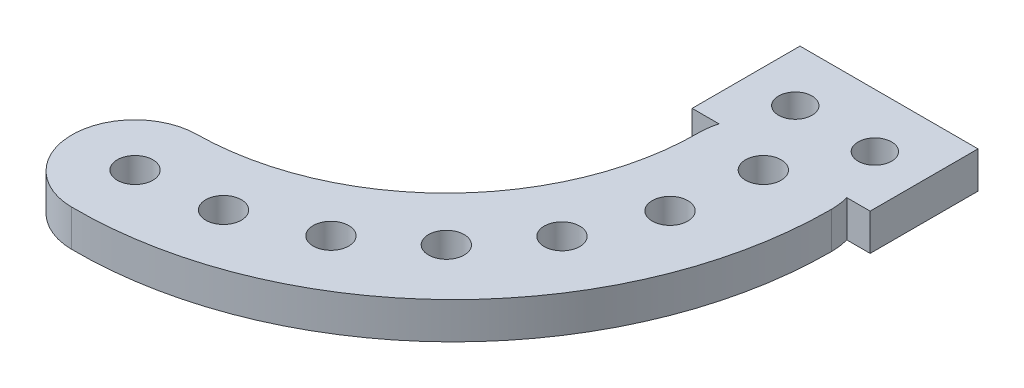
SolidWorks part; units mm, degrees
ref_plane "Plano frontal" through (0, 0, 0) normal (0, 0, 1) x (1, 0, 0)
ref_plane "Plano superior" through (0, 0, 0) normal (0, 1, 0) x (1, 0, 0)
ref_plane "Plano direito" through (0, 0, 0) normal (1, 0, 0) x (0, 0, -1)
sketch "Esboço1" plane through (0, 0, 0) normal (0, 1, 0) x (1, 0, 0)
  line L1 (-25, 5.5) -> (25, 5.5)
  line L2 (-25, 5.5) -> (-25, -5.5)
  line L3 (-25, -5.5) -> (25, -5.5)
  line L4 (25, 5.5) -> (25, -5.5)
  line L5 (-25, 5.5) -> (25, -5.5) construction
  line L6 (-25, -5.5) -> (25, 5.5) construction
  point P0 (0, 0)
  dimension "D1" = 50
  dimension "D2" = 11
extrude "Ressalto-extrusão1" add sketch "Esboço1" along normal blind 22.5
sketch "Esboço2" plane through (0, 22.5, 0) normal (0, 1, 0) x (1, 0, 0)
  line L1 (-23, 3.5) -> (23, 3.5)
  line L2 (-23, 3.5) -> (-23, -3.5)
  line L3 (-23, -3.5) -> (23, -3.5)
  line L4 (23, 3.5) -> (23, -3.5)
  line L5 (-23, 3.5) -> (23, -3.5) construction
  line L6 (-23, -3.5) -> (23, 3.5) construction
  point P0 (0, 0)
extrude "Corte-extrusão1" cut sketch "Esboço2" against normal blind 20.5
sketch "Esboço3" plane through (0, 22.5, 0) normal (0, 1, 0) x (1, 0, 0)
  line L3 (23, 3.5) -> (-23, 3.5) construction
  line L4 (-5.4896, 5.5) -> (5.4896, 5.5)
  line L5 (-5.4896, 5.5) -> (-5.4896, 3.5)
  line L6 (-5.4896, 3.5) -> (5.4896, 3.5)
  line L7 (5.4896, 5.5) -> (5.4896, 3.5)
  line L8 (-5.4896, 5.5) -> (5.4896, 3.5) construction
  line L9 (-5.4896, 3.5) -> (5.4896, 5.5) construction
  point P6 (0, 4.5)
extrude "Corte-extrusão2" cut sketch "Esboço3" against normal blind 4
sketch "Esboço5" plane through (0, 0, 5.5) normal (0, 0, 1) x (1, 0, 0)
  line L0 (-25, 22.5) -> (25, 22.5) construction
  line L1 (-21, 22.5) -> (-4.5, 22.5)
  line L2 (-21, 22.5) -> (-21, 11.75)
  line L4 (-4.5, 22.5) -> (-4.5, 11.75)
  line L5 (-25, 22.5) -> (-25, 0) construction
  line L7 (4.5, 22.5) -> (21, 22.5)
  line L8 (4.5, 22.5) -> (4.5, 11.75)
  line L10 (21, 22.5) -> (21, 11.75)
  line L11 (25, 22.5) -> (25, 0) construction
  arc A0 (-21, 11.75) -> (-4.5, 11.75) centre (-12.75, 11.75) ccw
  arc A1 (4.5, 11.75) -> (21, 11.75) centre (12.75, 11.75) ccw
  dimension "D1" = 16.5
  dimension "D2" = 4
  dimension "D3" = 16.5
  dimension "D4" = 4
  dimension "D6" = 0
extrude "Corte-extrusão3" cut sketch "Esboço5" against normal blind 4
sketch "Esboço9" plane through (0, 0, -5.5) normal (0, 0, -1) x (-1, 0, 0)
  line L0 (25, 22.5) -> (25, 0) construction
  line L1 (-25, 0) -> (25, 0)
  line L2 (-25, 0) -> (-25, 4)
  line L3 (-25, 4) -> (25, 4)
  line L4 (25, 0) -> (25, 4)
  dimension "D1" = 4
extrude "Ressalto-extrusão4" add sketch "Esboço9" along normal blind 7
sketch "Esboço13" plane through (0, 4, 0) normal (0, 1, 0) x (1, 0, 0)
  line L0 (25, 12.5) -> (25, 5.5) construction
  circle A0 centre (10, 9) radius 1.5
  circle A1 centre (5, 9) radius 1.5
  circle A2 centre (20, 9) radius 1.5
  circle A3 centre (15, 9) radius 1.5
  circle A4 centre (0, 9) radius 1.5
  circle A5 centre (-5, 9) radius 1.5
  circle A6 centre (-10, 9) radius 1.5
  circle A7 centre (-15, 9) radius 1.5
  circle A8 centre (-20, 9) radius 1.5
extrude "Corte-extrusão4" cut sketch "Esboço13" against normal blind 7
sketch "Esboço19" plane through (0, 22.5, 0) normal (0, 1, 0) x (1, 0, 0)
  line L0 (4.5, -3.5) -> (4.5, -5.5) construction
  line L1 (-4.5, -3.5) -> (4.5, -3.5)
  line L2 (-4.5, -3.5) -> (-4.5, -7.5)
  line L3 (-4.5, -7.5) -> (4.5, -7.5)
  line L4 (4.5, -3.5) -> (4.5, -7.5)
  point P4 (4.5, -4.5)
  dimension "D1" = 4
  dimension "D2" = 0
extrude "Ressalto-extrusão5" add sketch "Esboço19" against normal blind 22.5
ref_plane "Plano1" through (0, 32.5, 0) normal (0, 1, 0) x (1, 0, 0)
sketch "Esboço20" plane through (0, 32.5, 0) normal (0, 1, 0) x (1, 0, 0)
  line L0 (-15, -21) -> (-15, -15.1047) construction
  line L1 (25.584, -30.2923) -> (-27.4052, -30.2923)
  line L2 (25.584, -30.2923) -> (25.584, 21.1444)
  line L3 (25.584, 21.1444) -> (-27.4052, 21.1444)
  line L4 (-27.4052, -30.2923) -> (-27.4052, 21.1444)
  line L5 (-15, -21) -> (-21, -21) construction
  line L6 (-15, -21) -> (-15, -27.0897) construction
  line L7 (15, 9) -> (21.5, 9) construction
  line L8 (15, 9) -> (15, 15) construction
  line L9 (15, 9) -> (8.8338, 9) construction
  circle A1 centre (15, 9) radius 1.7
  circle A2 centre (-15, 9) radius 1.5 construction
  circle A3 centre (-15, 9) radius 1.5
  arc A4 (15, 9) -> (-15, -21) centre (-15, 9) cw
  circle A6 centre (20, 9) radius 1.5 construction
  arc A7 (8.8338, 9) -> (21.5, 9) centre (15.1669, 9.0036) cw
  arc A8 (-15, -15.1047) -> (-15, -27.0897) centre (-14.9357, -21.0972) ccw
  arc A9 (8.8338, 9) -> (-15, -15.1047) centre (-15.2587, 8.9864) cw
  arc A10 (21.5, 9) -> (-15, -27.0897) centre (-14.6122, 9.0204) cw
  circle A11 centre (-15, -21) radius 1.7
extrude "Ressalto-extrusão7" add sketch "Esboço20" along normal blind 3.5 separate body
sketch "Esboço21" plane through (0, 32.5, 0) normal (0, 1, 0) x (1, 0, 0)
  line L1 (34.2644, 29.8091) -> (-34.246, 29.8091)
  line L2 (34.2644, 29.8091) -> (34.2644, -37.0242)
  line L3 (34.2644, -37.0242) -> (-34.246, -37.0242)
  line L4 (-34.246, 29.8091) -> (-34.246, -37.0242)
extrude "Corte-extrusão7" cut sketch "Esboço21" against normal through all
sketch "Esboço22" plane through (0, 36, 0) normal (0, 1, 0) x (1, 0, 0)
  line L0 (-14.9357, -21.0972) -> (-15.2587, 8.9864) construction
  line L1 (15, 9) -> (-15.2587, 8.9864) construction
  line L2 (13.9251, 1.1666) -> (-15.2587, 8.9864) construction
  line L3 (10.8703, -6.0992) -> (-15.2587, 8.9864) construction
  line L4 (6.0501, -12.3224) -> (-15.2587, 8.9864) construction
  line L5 (-0.2048, -17.0878) -> (-15.2587, 8.9864) construction
  line L6 (-7.4706, -20.0791) -> (-15.2587, 8.9864) construction
  arc A0 (-14.9357, -21.0972) -> (15, 9) centre (-15.2606, 9.1621) ccw construction
  circle A2 centre (13.9251, 1.1666) radius 1.7
  circle A3 centre (10.8703, -6.0992) radius 1.7
  arc A4 (-15, -27.0897) -> (21.5, 9) centre (-14.6122, 9.0204) ccw
  arc A5 (21.5, 9) -> (8.8338, 9) centre (15.1669, 9.0036) ccw
  arc A6 (-15, -15.1047) -> (8.8338, 9) centre (-15.2587, 8.9864) ccw
  arc A7 (-15, -15.1047) -> (-15, -27.0897) centre (-14.9357, -21.0972) ccw
  arc A8 (-15, -27.0897) -> (21.5, 9) centre (-14.6122, 9.0204) ccw
  arc A9 (21.5, 9) -> (8.8338, 9) centre (15.1669, 9.0036) ccw
  arc A10 (-15, -15.1047) -> (8.8338, 9) centre (-15.2587, 8.9864) ccw
  arc A11 (-15, -15.1047) -> (-15, -27.0897) centre (-14.9357, -21.0972) ccw
  circle A12 centre (6.0501, -12.3224) radius 1.7
  circle A13 centre (-0.2048, -17.0878) radius 1.7
  circle A14 centre (-7.4706, -20.0791) radius 1.7
  dimension "D1" = 0
extrude "Corte-extrusão8" cut sketch "Esboço22" against normal through all contours A0 A13 | A0 A13 | A0 A14 | A0 A14 | A0 A12 | A0 A12 | A0 A3 | A0 A3 | A0 A2 | A0 A2
sketch "Esboço23" plane through (0, 36, 0) normal (0, 1, 0) x (1, 0, 0)
  line L0 (15, 10.7) -> (23.5, 10.7)
  line L1 (15, 10.7) -> (6.5, 10.7)
  line L2 (23.5, 10.7) -> (23.5, 21)
  line L3 (6.5, 21) -> (6.5, 10.7)
  line L4 (15, 9) -> (23.5, 9) construction
  line L10 (23.5, 21) -> (6.5, 21)
  circle A0 centre (15, 9) radius 1.7 construction
extrude "Ressalto-extrusão9" add sketch "Esboço23" against normal blind 3.5
sketch "Esboço24" plane through (0, 36, 0) normal (0, 1, 0) x (1, 0, 0)
  line L0 (23.5, 15.85) -> (18.8, 15.85) construction
  line L1 (6.5, 15.85) -> (11.2, 15.85) construction
  line L5 (21.2686, 10.7) -> (23.5, 10.7)
  line L6 (23.5, 10.7) -> (23.5, 21)
  line L7 (23.5, 21) -> (6.5, 21)
  line L8 (6.5, 21) -> (6.5, 10.7)
  line L9 (6.5, 10.7) -> (9.0652, 10.7)
  line L10 (21.2686, 10.7) -> (23.5, 10.7)
  line L11 (23.5, 10.7) -> (23.5, 21)
  line L13 (6.5, 21) -> (6.5, 10.7)
  line L14 (6.5, 10.7) -> (9.0652, 10.7)
  circle A0 centre (11.2, 15.85) radius 1.6
  circle A1 centre (18.8, 15.85) radius 1.6
  arc A5 (21.5, 9) -> (21.2686, 10.7) centre (15.1669, 9.0036) ccw
  arc A6 (9.0652, 10.7) -> (8.8338, 9) centre (15.1669, 9.0036) ccw
  arc A7 (-15, -15.1047) -> (8.8338, 9) centre (-15.2587, 8.9864) ccw
  arc A8 (-15, -15.1047) -> (-15, -27.0897) centre (-14.9357, -21.0972) ccw
  arc A9 (-15, -27.0897) -> (21.5, 9) centre (-14.6122, 9.0204) ccw
  arc A10 (21.5, 9) -> (21.2686, 10.7) centre (15.1669, 9.0036) ccw
  arc A11 (9.0652, 10.7) -> (8.8338, 9) centre (15.1669, 9.0036) ccw
  arc A12 (-15, -15.1047) -> (8.8338, 9) centre (-15.2587, 8.9864) ccw
  arc A13 (-15, -15.1047) -> (-15, -27.0897) centre (-14.9357, -21.0972) ccw
  arc A14 (-15, -27.0897) -> (21.5, 9) centre (-14.6122, 9.0204) ccw
  dimension "D1" = 0
extrude "Corte-extrusão9" cut sketch "Esboço24" against normal blind 3.5 contours A0 | A1
